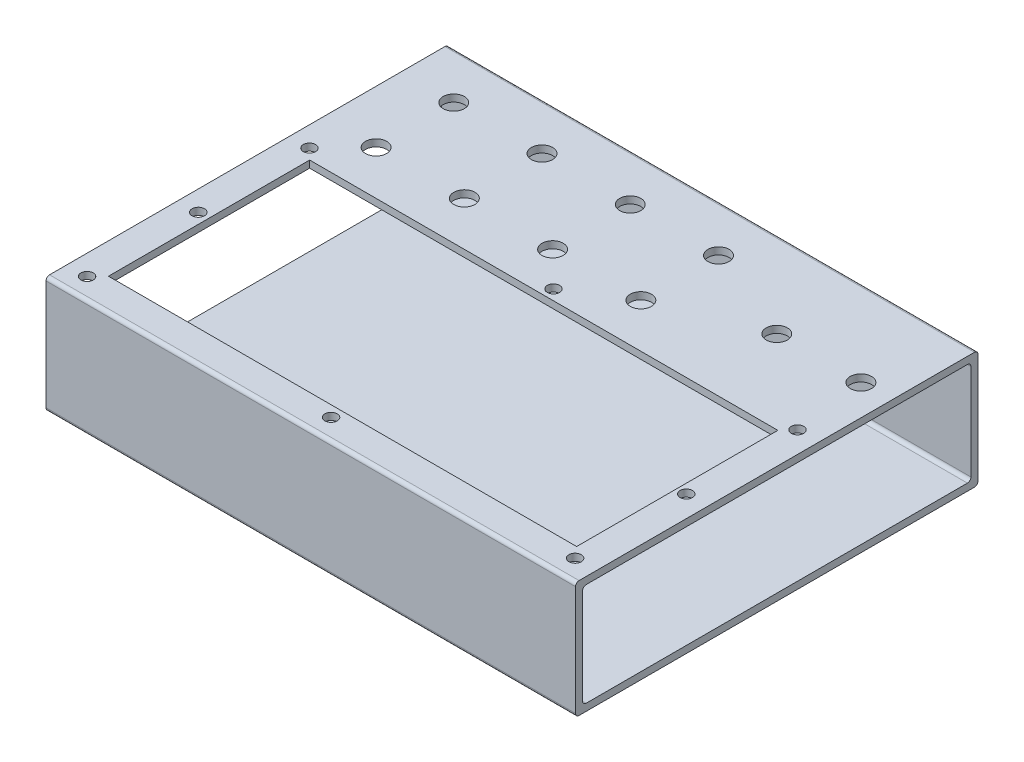
SolidWorks part; units mm, degrees
ref_plane "Front Plane" through (0, 0, 0) normal (0, 0, 1) x (1, 0, 0)
ref_plane "Top Plane" through (0, 0, 0) normal (0, 1, 0) x (1, 0, 0)
ref_plane "Right Plane" through (0, 0, 0) normal (1, 0, 0) x (0, 0, -1)
sketch "Sketch23" plane through (0, 0, 0) normal (1, 0, 0) x (0, 0, -1)
  line L1 (-56, 16.55) -> (56, 16.55)
  line L2 (-57, 15.55) -> (-57, -15.55)
  line L3 (-56, -16.55) -> (56, -16.55)
  line L4 (57, 15.55) -> (57, -15.55)
  line L5 (-57, 16.55) -> (57, -16.55) construction
  line L6 (-57, -16.55) -> (57, 16.55) construction
  arc A0 (56, -16.55) -> (57, -15.55) centre (56, -15.55) ccw
  arc A1 (57, 15.55) -> (56, 16.55) centre (56, 15.55) ccw
  arc A2 (-56, -16.55) -> (-57, -15.55) centre (-56, -15.55) cw
  arc A3 (-56, 16.55) -> (-57, 15.55) centre (-56, 15.55) ccw
  point P0 (0, 0)
  point P18 (0, 0)
  dimension "D3" = 1
  dimension "D1" = 114
  dimension "D2" = 33.1
extrude "Boss-Extrude7" add sketch "Sketch23" along normal blind 150
sketch "Sketch24" plane through (0, 0, 0) normal (-1, 0, 0) x (0, 0, 1)
  line L1 (54, -14.55) -> (-54, -14.55)
  line L2 (55, -13.55) -> (55, 13.55)
  line L3 (54, 14.55) -> (-54, 14.55)
  line L4 (-55, -13.55) -> (-55, 13.55)
  line L5 (55, -14.55) -> (-55, 14.55) construction
  line L6 (55, 14.55) -> (-55, -14.55) construction
  arc A0 (-54, -14.55) -> (-55, -13.55) centre (-54, -13.55) cw
  arc A1 (-55, 13.55) -> (-54, 14.55) centre (-54, 13.55) cw
  arc A2 (54, 14.55) -> (55, 13.55) centre (54, 13.55) cw
  arc A3 (54, -14.55) -> (55, -13.55) centre (54, -13.55) ccw
  point P0 (0, 0)
  dimension "D3" = 1
  dimension "D1" = 110
  dimension "D2" = 29.1
extrude "Cut-Extrude3" cut sketch "Sketch24" against normal blind 150 contours L1 A0 L4 A1 L3 A2 L2 A3
sketch "Sketch25" plane through (0, 16.55, 0) normal (0, 1, 0) x (1, 0, 0)
  line L1 (8.69, 9) -> (141.31, 9)
  line L2 (8.69, 9) -> (8.69, -48)
  line L3 (8.69, -48) -> (141.31, -48)
  line L4 (141.31, 9) -> (141.31, -48)
  line L5 (8.69, 9) -> (141.31, -48) construction
  line L6 (8.69, -48) -> (141.31, 9) construction
  line L7 (0, 56) -> (0, -56) construction
  line L8 (8.69, -19.5) -> (0, -19.5) construction
  line L9 (141.31, -19.5) -> (150, -19.5) construction
  line L10 (150, 56) -> (150, -56) construction
  line L11 (150, -56) -> (0, -56) construction
  point P0 (75, -19.5)
  dimension "D1" = 132.62
  dimension "D2" = 57
  dimension "D3" = 8
  dimension "D4" = 8.69
extrude "Cut-Extrude4" cut sketch "Sketch25" against normal blind 2
sketch "Sketch26" plane through (0, 16.55, 0) normal (0, 1, 0) x (1, 0, 0)
  line L0 (15, 43.5) -> (15, 21.5) construction
  line L1 (40, 43.5) -> (40, 21.5) construction
  line L2 (65, 43.5) -> (65, 21.5) construction
  line L3 (90, 43.5) -> (90, 21.5) construction
  line L4 (15, 32.5) -> (40, 32.5) construction
  line L5 (40, 32.5) -> (65, 32.5) construction
  line L6 (65, 32.5) -> (90, 32.5) construction
  line L7 (75, 56) -> (75, 9) construction
  line L8 (150, 56) -> (0, 56) construction
  line L9 (141.31, 9) -> (8.69, 9) construction
  line L10 (0, 56) -> (0, -56) construction
  line L11 (90, 32.5) -> (117.5, 32.5) construction
  line L12 (117.5, 32.5) -> (141.3335, 32.5) construction
  circle A0 centre (15, 43.5) radius 3
  circle A1 centre (15, 21.5) radius 3
  circle A2 centre (40, 43.5) radius 3
  circle A3 centre (40, 21.5) radius 3
  circle A4 centre (65, 43.5) radius 3
  circle A5 centre (65, 21.5) radius 3
  circle A6 centre (90, 43.5) radius 3
  circle A7 centre (90, 21.5) radius 3
  circle A8 centre (15, 43.5) radius 7.5 construction
  circle A9 centre (15, 21.5) radius 7.5 construction
  circle A10 centre (40, 43.5) radius 7.5 construction
  circle A11 centre (40, 21.5) radius 7.5 construction
  circle A12 centre (65, 43.5) radius 7.5 construction
  circle A13 centre (65, 21.5) radius 7.5 construction
  circle A14 centre (90, 43.5) radius 7.5 construction
  circle A15 centre (90, 21.5) radius 7.5 construction
  circle A16 centre (74.8403, 11.9103) radius 1.75
  circle A17 centre (5.7203, 11.9103) radius 1.75
  circle A18 centre (5.7203, -19.5897) radius 1.75
  circle A19 centre (5.7203, -51.0897) radius 1.75
  circle A20 centre (74.8403, -51.0897) radius 1.75
  circle A21 centre (143.9603, -51.0897) radius 1.75
  circle A22 centre (143.9603, -19.5897) radius 1.75
  circle A23 centre (143.9603, 11.9103) radius 1.75
  circle A24 centre (117.5, 32.5) radius 3
  circle A25 centre (117.5, 32.5) radius 16 construction
  circle A26 centre (141.3335, 32.5) radius 3
  point P26 (75, 32.5)
  dimension "D1" = 22
  dimension "D3" = 15
  dimension "D4" = 27.5
  dimension "D2" = 25
extrude "Cut-Extrude5" cut sketch "Sketch26" against normal blind 10
